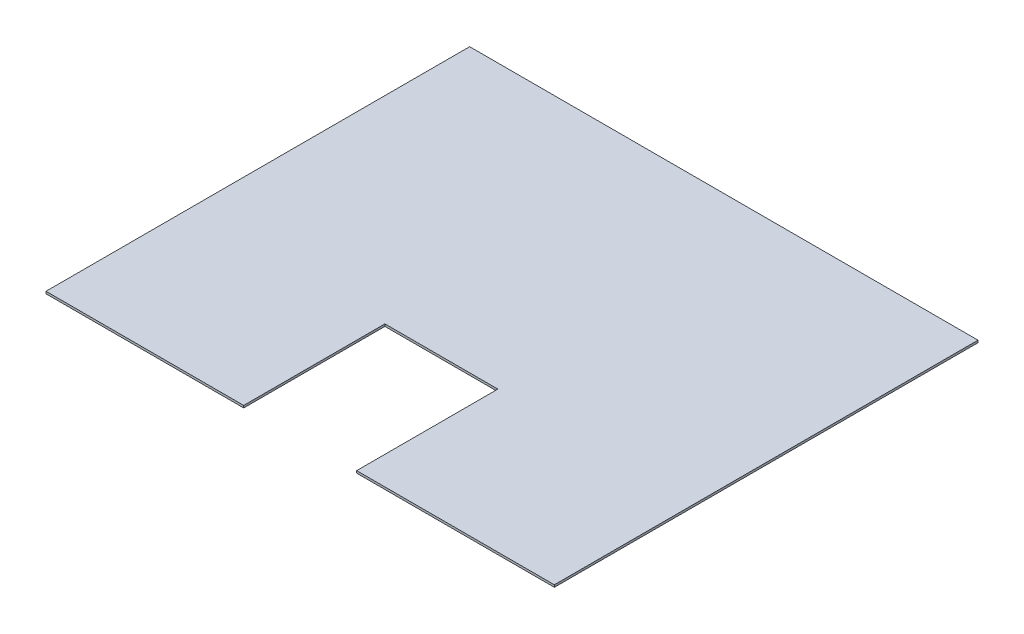
SolidWorks part; units mm, degrees
material "AISI 1035 Steel (SS)"
ref_plane "Front Plane" through (0, 0, 0) normal (0, 0, 1) x (1, 0, 0)
ref_plane "Top Plane" through (0, 0, 0) normal (0, 1, 0) x (1, 0, 0)
ref_plane "Right Plane" through (0, 0, 0) normal (1, 0, 0) x (0, 0, -1)
sketch "Sketch1" plane through (0, 0, 0) normal (0, 1, 0) x (1, 0, 0)
  line L1 (-228.6, 190.5) -> (228.6, 190.5)
  line L2 (-228.6, 190.5) -> (-228.6, -190.5)
  line L3 (-228.6, -190.5) -> (228.6, -190.5)
  line L4 (228.6, 190.5) -> (228.6, -190.5)
  line L5 (-228.6, 190.5) -> (228.6, -190.5) construction
  line L6 (-228.6, -190.5) -> (228.6, 190.5) construction
  point P0 (0, 0)
  dimension "D1" = 457.2
  dimension "D2" = 381
extrude "Boss-Extrude1" add sketch "Sketch1" along normal blind 2
sketch "Sketch120" plane through (0, 2, 0) normal (0, 1, 0) x (1, 0, 0)
  line L1 (-228.6, -190.5) -> (228.6, -190.5) construction
  line L2 (-50.8, -190.5) -> (-50.8, -63.5)
  line L3 (-50.8, -63.5) -> (50.8, -63.5)
  line L4 (50.8, -63.5) -> (50.8, -190.5)
  line L5 (50.8, -190.5) -> (-50.8, -190.5)
extrude "Cut-Extrude2" cut sketch "Sketch120" against normal through all
